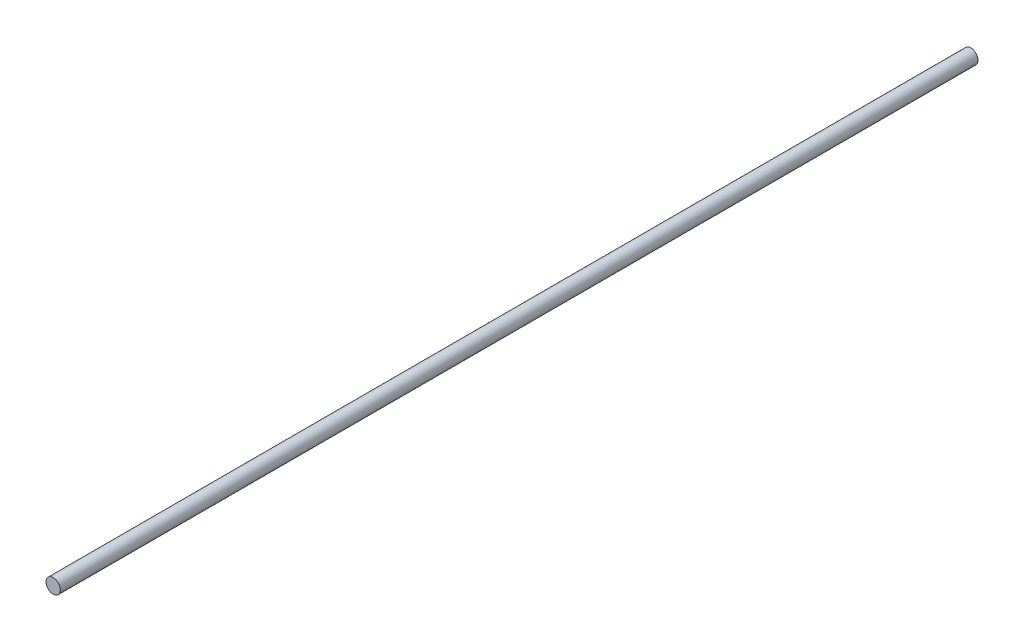
SolidWorks part; units mm, degrees
ref_plane "Front Plane" through (0, 0, 0) normal (0, 0, 1) x (1, 0, 0)
ref_plane "Top Plane" through (0, 0, 0) normal (0, 1, 0) x (1, 0, 0)
ref_plane "Right Plane" through (0, 0, 0) normal (1, 0, 0) x (0, 0, -1)
sketch "Sketch1" plane through (0, 0, 0) normal (0, 0, 1) x (1, 0, 0)
  circle A0 centre (0, 0) radius 2.3812
  point P4 (-2.3812, 0)
  dimension "Diameter" = 4.7625
sketch "Sketch2" plane through (0, 0, 0) normal (1, 0, 0) x (0, 0, -1)
  line L0 (-152.4, 0) -> (152.4, 0)
  line L1 (0, -2.3812) -> (0, 2.3812) construction
  line L2 (0, 2.3812) -> (0, -2.3812) construction
  line L3 (152.4, -2.3812) -> (152.4, 2.3813)
  line L4 (-152.4, -2.3812) -> (-152.4, 2.3813)
  point P0 (127, 0)
  point P4 (0, 0)
  point P6 (-127, 0)
  point P12 (0, 0)
  point P15 (152.4, 0)
  point P18 (-152.4, 0)
  dimension "D1" = 25.4
  dimension "Length" = 304.8
sketch "Sketch3" plane through (0, 0, 0) normal (0, 0, 1) x (1, 0, 0)
  circle A1 centre (0, 0) radius 2.3812
  circle A5 centre (0, 0) radius 2.3812
  dimension "D1" = 0
extrude "Boss-Extrude1" add sketch "Sketch3" along normal mid plane 304.8
equation "\"D1@Boss-Extrude1\"=\"Length@Sketch2\""
